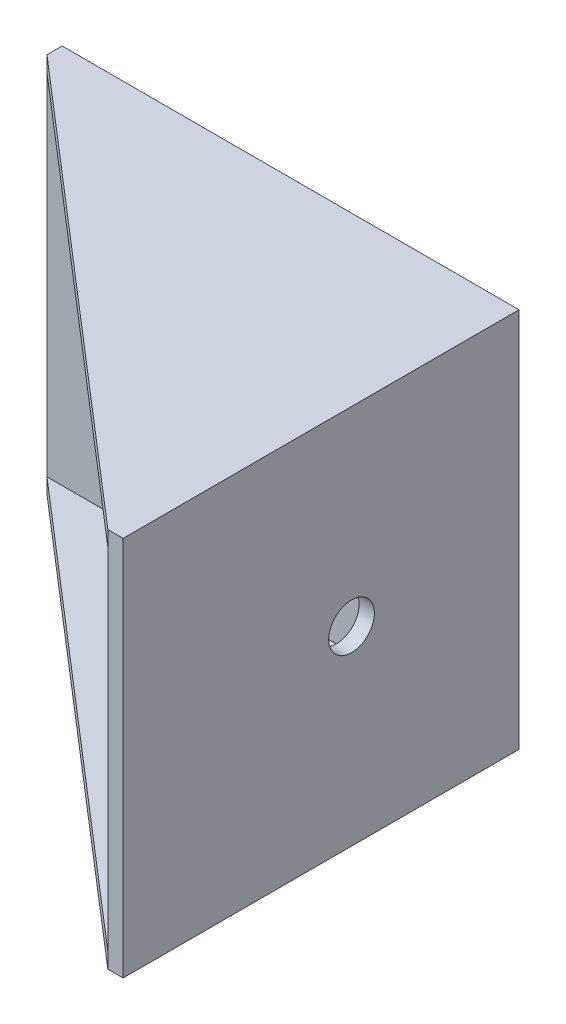
SolidWorks part; units mm, degrees
material "1060 Alloy"
ref_plane "Front Plane" through (0, 0, 0) normal (0, 0, 1) x (1, 0, 0)
ref_plane "Top Plane" through (0, 0, 0) normal (0, 1, 0) x (1, 0, 0)
ref_plane "Right Plane" through (0, 0, 0) normal (1, 0, 0) x (0, 0, -1)
sketch "Sketch1" plane through (0, 0, 0) normal (0, 0, 1) x (1, 0, 0)
  line L1 (-15, 12.5) -> (15, 12.5)
  line L2 (-15, 12.5) -> (-15, -12.5)
  line L3 (-15, -12.5) -> (15, -12.5)
  line L4 (15, 12.5) -> (15, -12.5)
  line L5 (-15, 12.5) -> (15, -12.5) construction
  line L6 (-15, -12.5) -> (15, 12.5) construction
  point P0 (0, 0)
  dimension "D1" = 25
  dimension "D2" = 30
extrude "Boss-Extrude1" add sketch "Sketch1" along normal blind 1
sketch "Sketch2" plane through (0, 0, 1) normal (0, 0, 1) x (1, 0, 0)
  line L0 (15, 12.5) -> (14, 12.5)
  line L1 (15, 12.5) -> (-15, 12.5) construction
  line L2 (14, 12.5) -> (14, -12.5)
  line L3 (-15, -12.5) -> (15, -12.5) construction
  line L4 (14, -12.5) -> (15, -12.5)
  line L5 (15, -12.5) -> (15, 12.5)
  dimension "D1" = 1
extrude "Boss-Extrude2" add sketch "Sketch2" along normal blind 25
sketch "Sketch6" plane through (0, -12.5, 0) normal (0, -1, 0) x (1, 0, 0)
  line L0 (14, 26) -> (-15, 1)
  line L1 (-15, 1) -> (14, 1)
  line L2 (14, 1) -> (14, 26)
extrude "Boss-Extrude3" add sketch "Sketch6" against normal blind 1
mirror "Mirror2" about plane through (0, 0, 0) normal (0, 1, 0) of "Boss-Extrude3"
sketch "Sketch7" plane through (14, 0, 0) normal (-1, 0, 0) x (0, 0, 1)
  line L0 (1, 11.5) -> (1, -11.5) construction
  circle A0 centre (11, 0) radius 1.5
  dimension "D1" = 10
extrude "Cut-Extrude1" cut sketch "Sketch7" against normal blind 3
